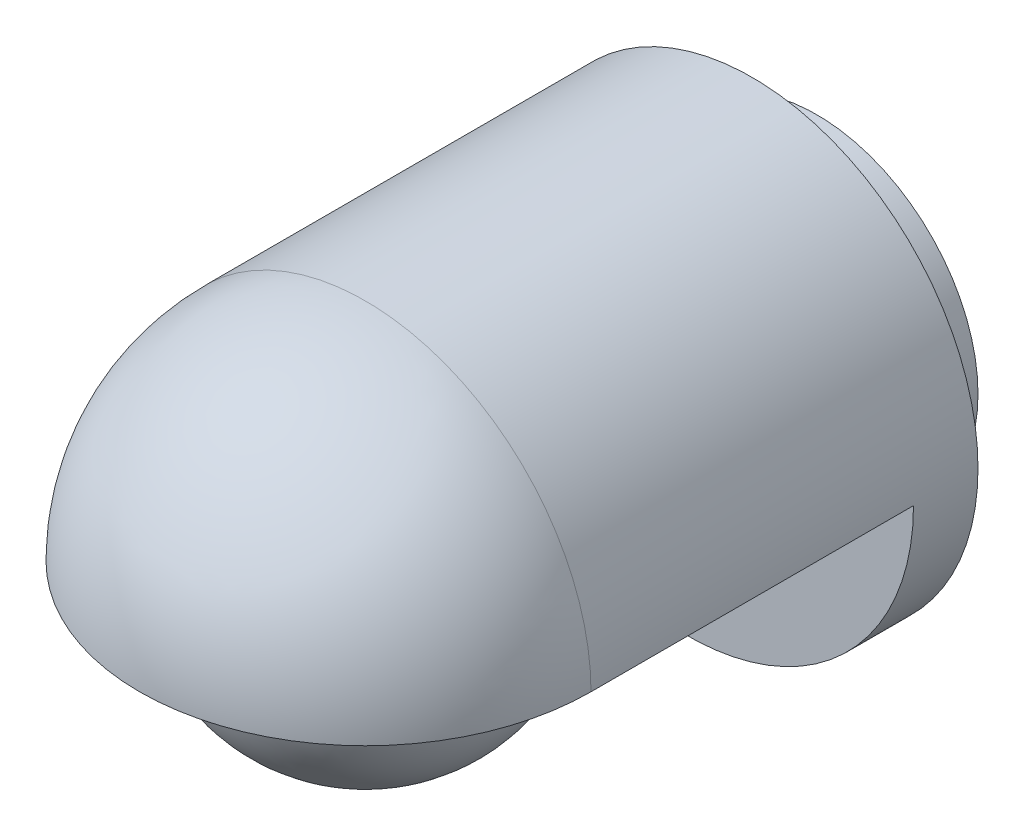
SolidWorks part; units mm, degrees
ref_plane "Front Plane" through (0, 0, 0) normal (0, 0, 1) x (1, 0, 0)
ref_plane "Top Plane" through (0, 0, 0) normal (0, 1, 0) x (1, 0, 0)
ref_plane "Right Plane" through (0, 0, 0) normal (1, 0, 0) x (0, 0, -1)
sketch "Sketch1" plane through (0, 0, 0) normal (0, 1, 0) x (1, 0, 0)
  line L0 (0, 50) -> (0, -50)
  arc A0 (0, 50) -> (0, -50) centre (0, 0) ccw
  dimension "D1" = 100
revolve "Revolve1" add sketch "Sketch1" angle 360 about L0
sketch "Sketch2" plane through (0, 0, 0) normal (0, 1, 0) x (1, 0, 0)
  line L0 (0, 120) -> (0, -70)
  line L1 (-70, 0) -> (0, 0)
  line L2 (-70, 0) -> (-70, 120)
  line L3 (-70, 120) -> (0, 120)
  arc A0 (-70, 0) -> (0, -70) centre (0, 0) ccw
  dimension "D1" = 140
revolve "Revolve2" add sketch "Sketch2" angle 180 about L0
sketch "Sketch3" plane through (0, 0, -120) normal (0, 0, -1) x (-1, 0, 0)
  circle A0 centre (0, 0) radius 50
extrude "Boss-Extrude1" add sketch "Sketch3" along normal blind 20 contours A0
sketch "Sketch4" plane through (0, 0, -120) normal (0, 0, -1) x (-1, 0, 0)
  circle A0 centre (0, 0) radius 70
extrude "Boss-Extrude2" add sketch "Sketch4" against normal blind 20 contours A0
